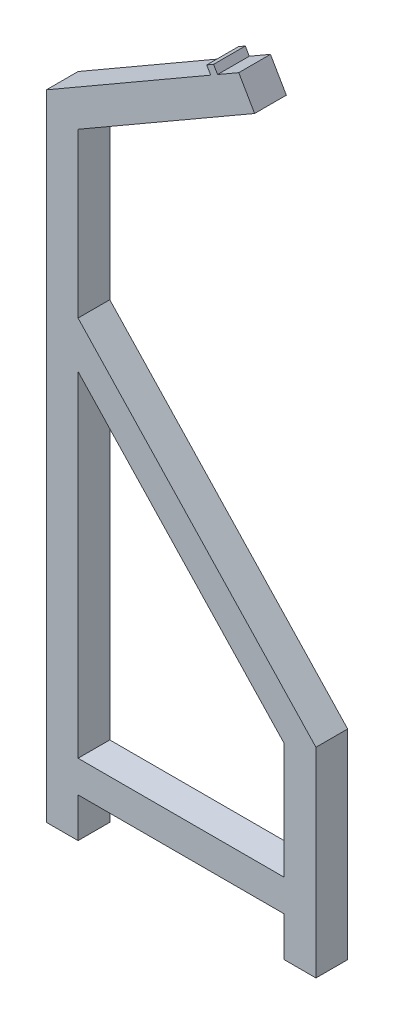
SolidWorks part; units mm, degrees
ref_plane "前视基准面" through (0, 0, 0) normal (0, 0, 1) x (1, 0, 0)
ref_plane "上视基准面" through (0, 0, 0) normal (0, 1, 0) x (1, 0, 0)
ref_plane "右视基准面" through (0, 0, 0) normal (1, 0, 0) x (0, 0, -1)
sketch "草图1" plane through (0, 0, 0) normal (0, 0, 1) x (1, 0, 0)
  line L0 (-163.0909, -166.0727) -> (-193.0909, -134.1972)
  line L1 (-197.0909, -191.2727) -> (-193.0909, -191.2727)
  line L2 (-197.0909, -191.2727) -> (-197.0909, -111.2727)
  line L4 (-193.0909, -191.2727) -> (-193.0909, -186.2727)
  line L5 (-167.0909, -191.2727) -> (-163.0909, -191.2727)
  line L6 (-167.0909, -191.2727) -> (-167.0909, -186.2727)
  line L8 (-163.0909, -191.2727) -> (-163.0909, -166.0727)
  line L9 (-193.0909, -186.2727) -> (-167.0909, -186.2727)
  line L11 (-193.0909, -182.2727) -> (-167.0909, -182.2727)
  line L15 (-167.0909, -167.659) -> (-193.0909, -140.0336)
  line L16 (-193.0909, -182.2727) -> (-193.0909, -140.0336)
  line L17 (-167.0909, -182.2727) -> (-167.0909, -167.659)
  line L18 (-197.0909, -111.2727) -> (-176.3636, -99.3058)
  line L20 (-172.8249, -97.2627) -> (-170.8249, -100.7268)
  line L21 (-193.0909, -113.5821) -> (-170.8249, -100.7268)
  line L23 (-175.4975, -98.8058) -> (-175.9975, -97.9398)
  line L24 (-176.3636, -99.3058) -> (-176.8636, -98.4398)
  line L25 (-175.9975, -97.9398) -> (-176.8636, -98.4398)
  line L26 (-193.0909, -134.1972) -> (-193.0909, -113.5821)
  line L27 (-175.4975, -98.8058) -> (-172.8249, -97.2627)
  point P12 (-195.0909, -191.2727)
  dimension "D1" = 4
  dimension "D2" = 80
  dimension "D3" = 4
  dimension "D4" = 25.2
  dimension "D5" = 26
  dimension "D6" = 5
  dimension "D7" = 4
  dimension "D9" = 5
  dimension "D12" = 28.02
  dimension "D13" = 1
  dimension "D14" = 1
extrude "凸台-拉伸1" add sketch "草图1" along normal blind 4
